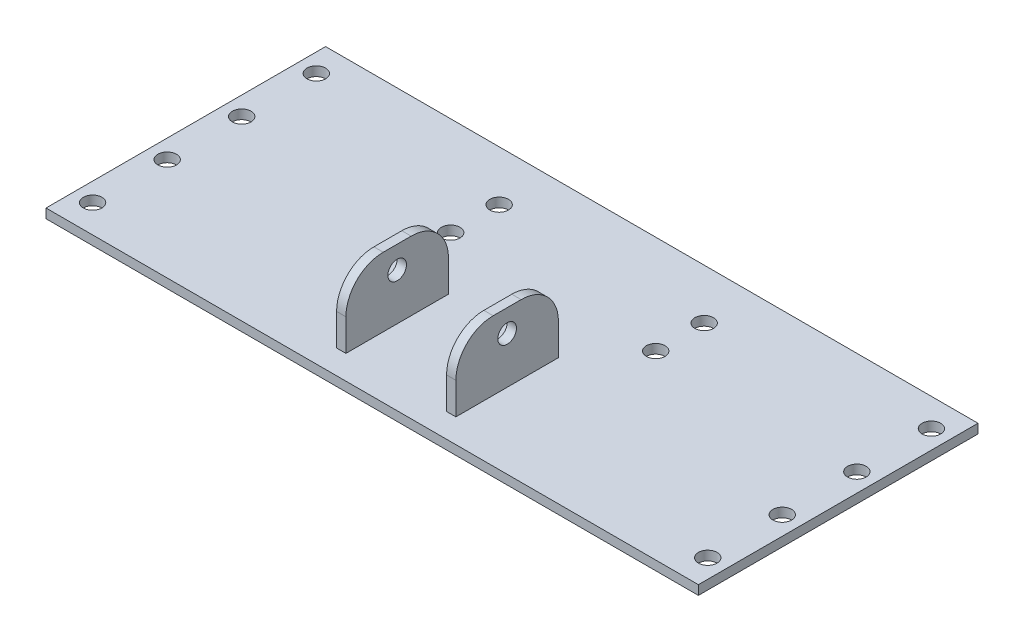
SolidWorks part; units mm, degrees
ref_plane "Front Plane" through (0, 0, 0) normal (0, 0, 1) x (1, 0, 0)
ref_plane "Top Plane" through (0, 0, 0) normal (0, 1, 0) x (1, 0, 0)
ref_plane "Right Plane" through (0, 0, 0) normal (1, 0, 0) x (0, 0, -1)
sketch "Sketch1" plane through (0, 0, 0) normal (0, 1, 0) x (1, 0, 0)
  line L1 (175, 75) -> (-175, 75)
  line L2 (175, 75) -> (175, -75)
  line L3 (175, -75) -> (-175, -75)
  line L4 (-175, 75) -> (-175, -75)
  line L5 (175, 75) -> (-175, -75) construction
  line L6 (175, -75) -> (-175, 75) construction
  point P0 (0, 0)
  dimension "D1" = 350
  dimension "D2" = 150
extrude "Boss-Extrude1" add sketch "Sketch1" along normal blind 5
ref_plane "Plane1" through (27, 0, 0) normal (1, 0, 0) x (0, 0, -1)
sketch "Sketch2" plane through (27, 0, 0) normal (1, 0, 0) x (0, 0, -1)
  line L0 (-75, 5) -> (-75, 0) construction
  line L1 (-62.1, 0) -> (-7.1, 0)
  line L2 (-62.1, 0) -> (-62.1, 42)
  line L3 (-62.1, 42) -> (-7.1, 42)
  line L4 (-7.1, 0) -> (-7.1, 42)
  dimension "D1" = 55
  dimension "D2" = 42
  dimension "D3" = 12.9
extrude "Boss-Extrude2" add sketch "Sketch2" along normal blind 5
sketch "Sketch3" plane through (32, 0, 0) normal (1, 0, 0) x (0, 0, -1)
  line L0 (-34.6, 42) -> (-34.6, -13.6308) construction
  line L1 (-7.1, 42) -> (-62.1, 42) construction
  line L2 (-62.1, 5) -> (-7.1, 5) construction
  circle A0 centre (-34.6, 30) radius 5
  dimension "D1" = 10
  dimension "D2" = 25
  dimension "D3" = 12
extrude "Cut-Extrude1" cut sketch "Sketch3" against normal through all
fillet "Fillet1" radius 20 2 edges at (29.5, 42, 7.1) (29.5, 42, 62.1)
mirror "Mirror1" about plane through (0, 0, 0) normal (1, 0, 0) of "Boss-Extrude2", "Cut-Extrude1", "Fillet1"
sketch "Sketch5" plane through (0, 5, 0) normal (0, 1, 0) x (1, 0, 0)
  line L0 (-55, 85.7024) -> (-55, -89.6518) construction
  line L1 (-198.4583, 48.1) -> (189.7696, 48.1) construction
  line L2 (-198.4583, 22.1) -> (212.6762, 22.1) construction
  line L3 (175, 75) -> (-175, 75) construction
  circle A0 centre (-55, 48.1) radius 5
  circle A1 centre (-55, 22.1) radius 5
  dimension "D4" = 10
  dimension "D1" = 55
  dimension "D2" = 26.9
  dimension "D3" = 26
extrude "Cut-Extrude3" cut sketch "Sketch5" against normal through all
mirror "Mirror3" about plane through (0, 0, 0) normal (1, 0, 0) of "Cut-Extrude3"
sketch "Sketch6" plane through (0, 5, 0) normal (0, 1, 0) x (1, 0, 0)
  line L0 (-165, 105.8444) -> (-165, -94.3911) construction
  line L1 (-195.2987, 60) -> (181.0808, 60) construction
  line L2 (-195.2987, 20) -> (188.9797, 20) construction
  line L3 (-195.2987, -20) -> (188.9797, -20) construction
  line L4 (175, 75) -> (-175, 75) construction
  line L5 (-195.2987, -60) -> (193.324, -60) construction
  line L6 (-175, -75) -> (175, -75) construction
  line L7 (-175, 75) -> (-175, -75) construction
  circle A0 centre (-165, 60) radius 5
  circle A1 centre (-165, 20) radius 5
  circle A2 centre (-165, -20) radius 5
  circle A3 centre (-165, -60) radius 5
  dimension "D6" = 10
  dimension "D1" = 15
  dimension "D2" = 40
  dimension "D3" = 40
  dimension "D4" = 40
  dimension "D5" = 15
  dimension "D7" = 10
extrude "Cut-Extrude4" cut sketch "Sketch6" against normal through all
mirror "Mirror4" about plane through (0, 0, 0) normal (1, 0, 0) of "Cut-Extrude4"
